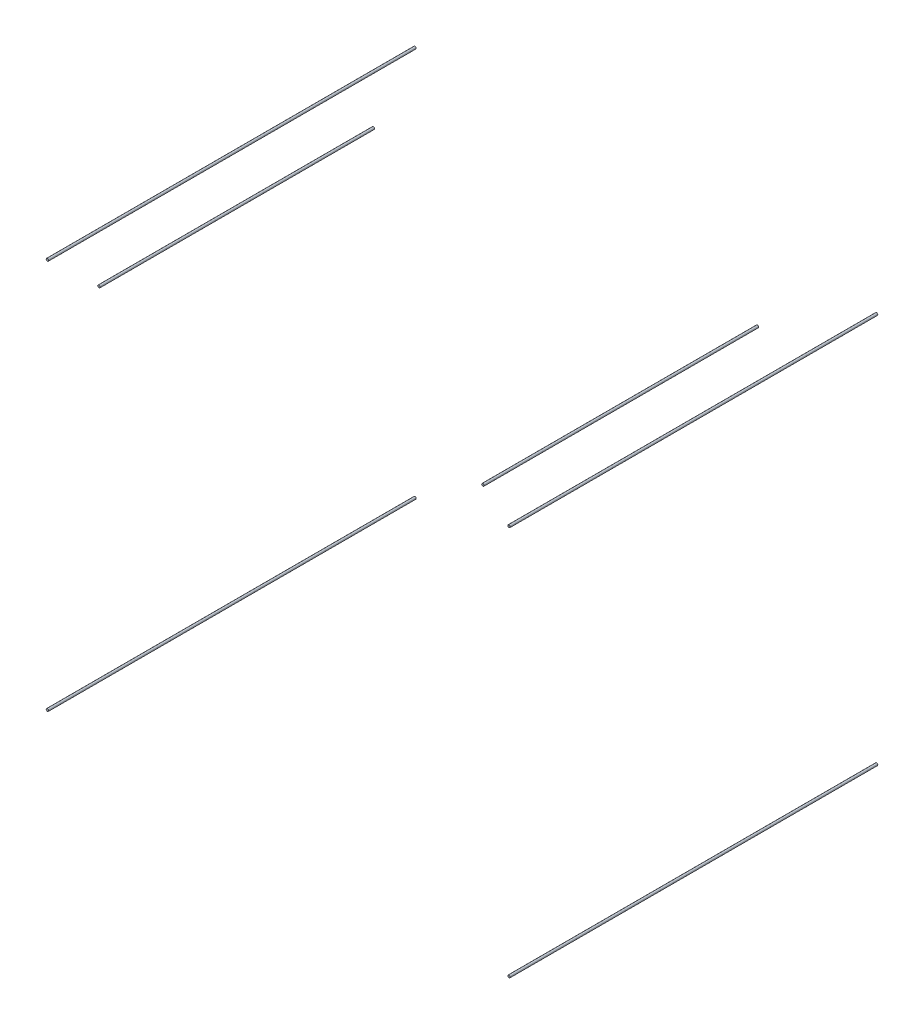
SolidWorks part; units mm, degrees
ref_plane "Front Plane" through (0, 0, 0) normal (0, 0, 1) x (1, 0, 0)
ref_plane "Top Plane" through (0, 0, 0) normal (0, 1, 0) x (1, 0, 0)
ref_plane "Right Plane" through (0, 0, 0) normal (1, 0, 0) x (0, 0, -1)
sketch "Sketch1" plane through (0, 0, 0) normal (0, 0, 1) x (1, 0, 0)
  circle A0 centre (3.5, 3.5) radius 0.15
  circle A1 centre (61.5, 3.5) radius 0.15
  circle A2 centre (3.5, 52.5) radius 0.15
  circle A3 centre (61.5, 52.5) radius 0.15
extrude "Line_1" add sketch "Sketch1" along normal blind 46.2
ref_plane "Plane_z10_1" through (0, 0, 10.1) normal (0, 0, 1) x (1, 0, 0)
sketch "Sketch2" plane through (0, 0, 10.1) normal (0, 0, 1) x (1, 0, 0)
  circle A0 centre (8.37, 51.23) radius 0.15
  circle A1 centre (56.63, 53.77) radius 0.15
extrude "Line_2" add sketch "Sketch2" along normal blind 34.5
